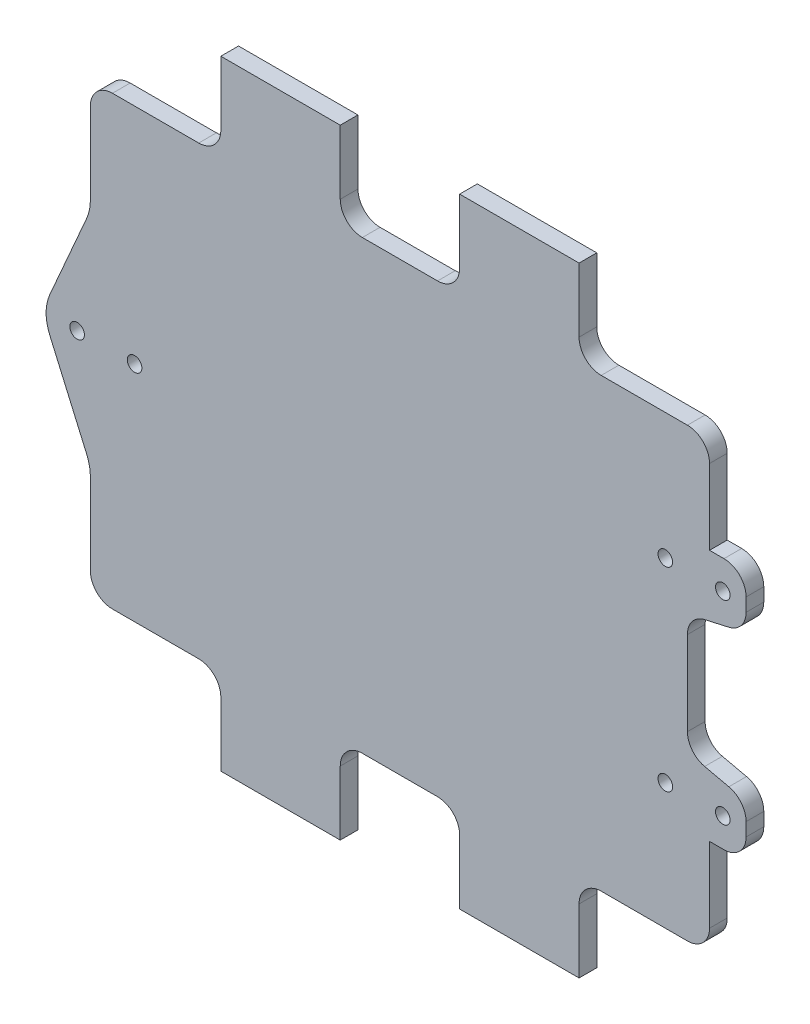
SolidWorks part; units mm, degrees
material "Ceramic Porcelain"
ref_plane "Front Plane" through (0, 0, 0) normal (0, 0, 1) x (1, 0, 0)
ref_plane "Top Plane" through (0, 0, 0) normal (0, 1, 0) x (1, 0, 0)
ref_plane "Right Plane" through (0, 0, 0) normal (1, 0, 0) x (0, 0, -1)
sketch "Sketch1" plane through (0, 0, 0) normal (0, 0, 1) x (1, 0, 0)
  line L0 (135, 70) -> (-19.1725, 70) construction
  line L1 (0, 0) -> (135, 0)
  line L2 (0, 0) -> (0, 42.9273)
  line L3 (0, 140) -> (135, 140)
  line L4 (135, 0) -> (135, 140)
  line L5 (-9.164, 74.0025) -> (-0.836, 93.0702)
  line L6 (-9.164, 65.9975) -> (-0.836, 46.9298)
  line L7 (0, 97.0727) -> (0, 140)
  line L8 (0, 97.0727) -> (0, 42.9273) construction
  arc A0 (-9.164, 65.9975) -> (-9.164, 74.0025) centre (0, 70) cw
  arc A1 (-0.836, 93.0702) -> (0, 97.0727) centre (-10, 97.0727) ccw
  arc A2 (-0.836, 46.9298) -> (0, 42.9273) centre (-10, 42.9273) cw
  point P14 (0, 94.9841)
  dimension "D2" = 10
  dimension "D3" = 10
  dimension "D4" = 10
  dimension "D1" = 140
  dimension "D5" = 135
extrude "Boss-Extrude1" add sketch "Sketch1" along normal blind 4
sketch "Sketch2" plane through (0, 0, 4) normal (0, 0, 1) x (1, 0, 0)
  line L0 (0, 42.9273) -> (0, 0) construction
  line L1 (5, 5) -> (27, 5)
  line L2 (5, 5) -> (5, 27)
  line L3 (5, 27) -> (27, 27)
  line L4 (27, 5) -> (27, 27)
  line L5 (0, 0) -> (135, 0) construction
  dimension "D1" = 22
  dimension "D2" = 5
  dimension "D3" = 5
extrude "Cut-Extrude2" [suppressed] cut sketch "Sketch2" against normal blind 3
chamfer "Chamfer1" [suppressed] distance 3 angle 15
fillet "Fillet3" [suppressed] radius 1
fillet "Fillet4" [suppressed] radius 1
pattern_linear "LPattern1" [suppressed] count 5 spacing 27 count 5 spacing 27
sketch "Sketch3" plane through (0, 0, 4) normal (0, 0, 1) x (1, 0, 0)
  line L0 (0, 0) -> (135, 0) construction
  line L1 (0, 0) -> (29.5, 0)
  line L2 (0, 0) -> (0, 19.5)
  line L3 (0, 19.5) -> (29.5, 19.5)
  line L4 (29.5, 0) -> (29.5, 19.5)
  line L5 (56.5, 0) -> (83.5, 0)
  line L6 (56.5, 0) -> (56.5, 19.5)
  line L7 (56.5, 19.5) -> (83.5, 19.5)
  line L8 (83.5, 0) -> (83.5, 19.5)
  line L9 (70, 0) -> (70, 140) construction
  line L10 (140, 140) -> (110.5, 140)
  line L11 (140, 140) -> (140, 120.5)
  line L15 (110.5, 0) -> (110.5, 19.5)
  line L16 (140, 19.5) -> (110.5, 19.5)
  line L17 (140, 0) -> (140, 19.5)
  line L18 (140, 0) -> (110.5, 0)
  line L19 (140, 120.5) -> (110.5, 120.5)
  line L20 (110.5, 140) -> (110.5, 120.5)
  line L21 (29.5, 140) -> (29.5, 120.5)
  line L22 (0, 120.5) -> (29.5, 120.5)
  line L23 (0, 140) -> (0, 120.5)
  line L24 (0, 140) -> (29.5, 140)
  line L25 (0, 0) -> (140, 140) construction
  line L31 (83.5, 140) -> (83.5, 120.5)
  line L32 (56.5, 120.5) -> (83.5, 120.5)
  line L33 (56.5, 140) -> (56.5, 120.5)
  line L34 (56.5, 140) -> (83.5, 140)
  dimension "D1" = 19.5
  dimension "D2" = 56.5
  dimension "D3" = 27
  dimension "D4" = 29.5
extrude "Cut-Extrude3" cut sketch "Sketch3" against normal through all
sketch "Sketch9" plane through (0, 0, 0) normal (0, 0, -1) x (-1, 0, 0)
  line L0 (-140, 98.5) -> (-148.2665, 98.5)
  line L1 (-148.2665, 98.5) -> (-148.2665, 86.5)
  line L2 (-148.2665, 86.5) -> (-135, 83.5)
  line L3 (-135, 19.5) -> (-135, 120.5) construction
  line L4 (-135, 70) -> (-101.7414, 70) construction
  line L5 (-135, 105.5) -> (-135, 83.5)
  line L6 (-140, 19.5) -> (-140, 41.5)
  line L7 (-135, 19.5) -> (-135, 34.5)
  line L8 (-135, 19.5) -> (-140, 19.5)
  line L9 (-135, 34.5) -> (-135, 56.5)
  line L10 (-110.5, 120.5) -> (-135, 120.5) construction
  line L11 (-148.2665, 53.5) -> (-135, 56.5)
  line L12 (-135, 120.5) -> (-140, 120.5)
  line L13 (-135, 120.5) -> (-135, 105.5)
  line L14 (-148.2665, 41.5) -> (-148.2665, 53.5)
  line L15 (-140, 120.5) -> (-140, 98.5)
  line L16 (-140, 41.5) -> (-148.2665, 41.5)
  dimension "D1" = 15
  dimension "D2" = 12
  dimension "D3" = 15
  dimension "D4" = 22
  dimension "D5" = 5
extrude "Boss-Extrude2" add sketch "Sketch9" against normal up to surface (4 mm away) up to face at (52.6761, 70, 4)
fillet "Fillet5" radius 5 6 edges at (148.2665, 86.5, 2) (148.2665, 98.5, 2) (148.2665, 41.5, 2) (148.2665, 53.5, 2) (135, 56.5, 2)
sketch "Sketch10" [suppressed] plane through (0, 0, 6) normal (0, 0, 1) x (1, 0, 0)
  line L0 (127.2327, 102) -> (127.2327, 108.7673)
  line L1 (112.2327, 108.7673) -> (135.7673, 108.7673) construction
  line L2 (127.2327, 108.7673) -> (135.7673, 108.7673)
  line L3 (134, 95.2327) -> (135.7673, 95.2327)
  line L4 (135.7673, 108.7673) -> (135.7673, 85.2327) construction
  line L5 (135.7673, 95.2327) -> (135.7673, 108.7673)
  line L6 (127.2327, 38) -> (127.2327, 31.2327)
  line L7 (135.7673, 31.2327) -> (112.2327, 31.2327) construction
  line L8 (127.2327, 31.2327) -> (135.7673, 31.2327)
  line L9 (135.7673, 31.2327) -> (135.7673, 44.7673)
  line L10 (135.7673, 54.7673) -> (135.7673, 31.2327) construction
  line L11 (135.7673, 44.7673) -> (134, 44.7673)
  line L12 (4.2327, 74.1422) -> (6, 74.1422)
  line L13 (4.2327, 58.2327) -> (4.2327, 81.7673) construction
  line L14 (4.2327, 74.1422) -> (4.2327, 65.8578)
  line L15 (4.2327, 65.8578) -> (6, 65.8578)
  arc A1 (134, 44.7673) -> (127.2327, 38) centre (134, 38) ccw
  arc A2 (6, 65.8578) -> (6, 74.1422) centre (6, 70) ccw
  arc A3 (127.2327, 102) -> (134, 95.2327) centre (134, 102) ccw
extrude "Boss-Extrude3" [suppressed] add sketch "Sketch10" against normal up to surface (3 mm away)
hole_wizard "CSK for M3 Flat Head Machine Screw1" positions "Sketch6" profile "Sketch5" countersink size "M3" standard "Ansi Metric" end condition through all
sketch "Sketch6" plane through (0, 0, 0) normal (0, 0, -1) x (-1, 0, 0)
  line L0 (3.5733, 70) -> (-135, 70) construction
  line L5 (-130, 92) -> (-130, 48) construction
  line L6 (-135, 60.4956) -> (-135, 79.5044) construction
  line L8 (-140, 98.5) -> (-140, 120.5) construction
  point P0 (-10, 70)
  point P20 (-130, 92)
  point P22 (-130, 48)
  dimension "D1" = 10
  dimension "D2" = 10
  dimension "D3" = 22
  dimension "D4" = 44
sketch "Sketch5" plane through (10, 70, 0) normal (1, 0, 0) x (0, 1, 0)
  line L0 (0, 0) -> (0, 4)
  line L1 (0, 4) -> (1.65, 4)
  line L2 (1.65, 4) -> (1.65, 1.35)
  line L3 (1.65, 1.35) -> (3, 0)
  line L5 (3, 0) -> (0, 0)
  line L6 (-1.65, 1.35) -> (-3, 0) construction
  line L11 (0, -6.35) -> (0, 107.95) construction
  dimension "Thru Hole Dia." = 3.3
  dimension "Thru Hole Depth" = 4
  dimension "Near C'Sink Dia." = 6
  dimension "Near C'Sink Angle" = 90
sketch "Sketch8" plane through (0, 0, 0) normal (0, 0, -1) x (-1, 0, 0)
  line L0 (-135, 70) -> (10, 70) construction
  line L2 (-130, 92) -> (-143, 92) construction
  line L3 (-130, 48) -> (-143, 48) construction
  line L4 (-135, 60.4956) -> (-135, 79.5044) construction
  arc A0 (9.164, 65.9975) -> (9.164, 74.0025) centre (0, 70) ccw construction
  circle A1 centre (3, 70) radius 1.65
  circle A2 centre (-10, 70) radius 1.65 construction
  circle A3 centre (-143, 92) radius 1.65
  circle A4 centre (-143, 48) radius 1.65
  dimension "D1" = 13
  dimension "D2" = 3.3
  dimension "D3" = 13
extrude "Cut-Extrude4" cut sketch "Sketch8" against normal through all
fillet "Fillet6" radius 5 12 edges at (29.5, 19.5, 2) (83.5, 19.5, 2) (56.5, 19.5, 2) (110.5, 19.5, 2) (29.5, 120.5, 2) (83.5, 120.5, 2) (56.5, 120.5, 2) (110.5, 120.5, 2) (0, 120.5, 2) (0, 19.5, 2) (140, 19.5, 2) (140, 120.5, 2)
sketch "Sketch11" plane through (0, 0, 4) normal (0, 0, 1) x (1, 0, 0)
  line L0 (135, 70) -> (-10, 70) construction
  line L1 (135, 60.4956) -> (135, 79.5044) construction
  line L2 (110.5872, 104.7584) -> (5.6009, 104.7584)
  line L3 (5.6009, 104.7584) -> (18.3195, 74.9275)
  line L4 (18.3195, 74.9275) -> (110.5872, 104.7584)
  line L5 (117.0488, 98.8234) -> (43.1382, 74.9275)
  line L6 (43.1382, 74.9275) -> (127.237, 74.9275)
  line L7 (127.237, 74.9275) -> (117.0488, 98.8234)
  line L8 (127.237, 65.0725) -> (117.0488, 41.1766)
  line L9 (43.1382, 65.0725) -> (127.237, 65.0725)
  line L10 (117.0488, 41.1766) -> (43.1382, 65.0725)
  line L11 (18.3195, 65.0725) -> (110.5872, 35.2416)
  line L12 (5.6009, 35.2416) -> (18.3195, 65.0725)
  line L13 (110.5872, 35.2416) -> (5.6009, 35.2416)
  arc A0 (-9.164, 74.0025) -> (-9.164, 65.9975) centre (0, 70) ccw construction
extrude "Cut-Extrude5" [suppressed] cut sketch "Sketch11" against normal offset from surface (3 mm away) 1
chamfer "Chamfer2" [suppressed] distance 3 angle 5
fillet "Fillet7" [suppressed] radius 1
